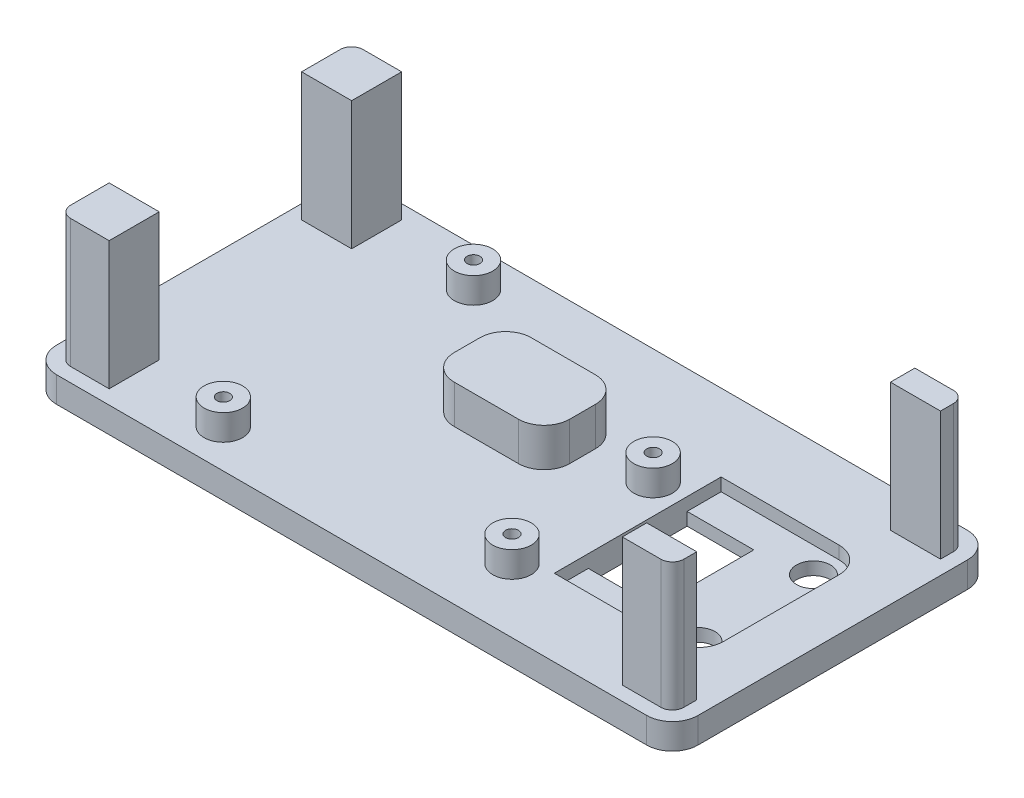
SolidWorks part; units mm, degrees
ref_plane "Front Plane" through (0, 0, 0) normal (0, 0, 1) x (1, 0, 0)
ref_plane "Top Plane" through (0, 0, 0) normal (0, 1, 0) x (1, 0, 0)
ref_plane "Right Plane" through (0, 0, 0) normal (1, 0, 0) x (0, 0, -1)
sketch "Sketch1" plane through (0, 0, 0) normal (0, 1, 0) x (1, 0, 0)
  line L1 (0, 0) -> (127, 0)
  line L2 (0, 0) -> (0, 63.5)
  line L3 (0, 63.5) -> (127, 63.5)
  line L4 (127, 0) -> (127, 63.5)
  dimension "D1" = 127
  dimension "D2" = 63.5
extrude "Boss-Extrude1" add sketch "Sketch1" along normal blind 5.08
sketch "Sketch2" plane through (0, 5.08, 0) normal (0, 1, 0) x (1, 0, 0)
  line L0 (63.5, 63.5) -> (63.5, 0) construction
  line L1 (127, 63.5) -> (0, 63.5) construction
  line L2 (0, 0) -> (127, 0) construction
  line L3 (0, 31.75) -> (127, 31.75) construction
  line L4 (0, 63.5) -> (0, 0) construction
  line L5 (127, 0) -> (127, 63.5) construction
  line L6 (12.7, 2.794) -> (12.7, 12.7)
  line L7 (2.794, 60.706) -> (12.7, 60.706)
  line L8 (2.794, 60.706) -> (2.794, 50.8)
  line L9 (2.794, 50.8) -> (12.7, 50.8)
  line L10 (12.7, 60.706) -> (12.7, 50.8)
  line L11 (2.794, 12.7) -> (12.7, 12.7)
  line L12 (2.794, 2.794) -> (2.794, 12.7)
  line L13 (2.794, 2.794) -> (12.7, 2.794)
  line L14 (124.206, 2.794) -> (124.206, 7.62)
  line L15 (114.3, 60.706) -> (124.206, 60.706)
  line L16 (114.3, 60.706) -> (114.3, 55.88)
  line L17 (114.3, 55.88) -> (124.206, 55.88)
  line L18 (124.206, 60.706) -> (124.206, 55.88)
  line L19 (114.3, 7.62) -> (124.206, 7.62)
  line L20 (114.3, 2.794) -> (114.3, 7.62)
  line L21 (114.3, 2.794) -> (124.206, 2.794)
  dimension "D1" = 9.906
  dimension "D2" = 9.906
  dimension "D3" = 2.794
  dimension "D4" = 2.794
  dimension "D5" = 2.794
  dimension "D6" = 2.794
  dimension "D7" = 4.826
  dimension "D8" = 9.906
extrude "Boss-Extrude3" add sketch "Sketch2" along normal blind 25.4
fillet "Fillet3" radius 2.286 4 edges at (124.206, 17.78, -60.706) (124.206, 17.78, -2.794) (2.794, 17.78, -2.794) (2.794, 17.78, -60.706)
fillet "Fillet4" radius 5.08 4 edges at (0, 2.54, -63.5) (127, 2.54, -63.5) (127, 2.54, 0) (0, 2.54, 0)
sketch "Sketch4" plane through (0, 5.08, 0) normal (0, 1, 0) x (1, 0, 0)
  circle A0 centre (31.75, 55.88) radius 3.81
  circle A1 centre (30.48, 7.62) radius 3.81
  circle A2 centre (82.55, 40.64) radius 3.81
  circle A3 centre (82.55, 12.7) radius 3.81
  circle A4 centre (31.75, 55.88) radius 1.27
  circle A5 centre (82.55, 40.64) radius 1.27
  circle A6 centre (30.48, 7.62) radius 1.27
  circle A7 centre (82.55, 12.7) radius 1.27
  dimension "D1" = 7.62
  dimension "D2" = 7.62
  dimension "D7" = 50.8
  dimension "D11" = 7.62
  dimension "D12" = 7.62
  dimension "D13" = 2.54
  dimension "D8" = 2.54
  dimension "D14" = 2.54
  dimension "D15" = 2.54
  dimension "D3" = 15.24
  dimension "D4" = 19.05
  dimension "D5" = 48.26
  dimension "D6" = 7.62
  dimension "D9" = 27.94
  dimension "D10" = 52.07
sketch "Sketch7" plane through (0, 5.08, 0) normal (0, 1, 0) x (1, 0, 0)
  line L0 (121.92, 63.5) -> (5.08, 63.5) construction
  line L1 (48.26, 45.72) -> (71.12, 45.72)
  line L2 (48.26, 45.72) -> (48.26, 30.48)
  line L3 (48.26, 30.48) -> (71.12, 30.48)
  line L4 (71.12, 45.72) -> (71.12, 30.48)
  dimension "D1" = 22.86
  dimension "D2" = 17.78
  dimension "D3" = 30.48
  dimension "D4" = 43.18
sketch "Sketch13" plane through (0, 5.08, 0) normal (0, 1, 0) x (1, 0, 0)
  line L0 (121.92, 63.5) -> (5.08, 63.5) construction
  line L1 (5.08, 0) -> (121.92, 0) construction
  line L2 (127, 5.08) -> (127, 58.42) construction
  line L4 (88.392, 41.529) -> (101.6, 41.529)
  line L5 (88.392, 41.529) -> (88.392, 21.971)
  line L6 (88.392, 21.971) -> (101.6, 21.971)
  line L7 (101.6, 41.529) -> (101.6, 21.971)
  circle A0 centre (111.76, 43.18) radius 3.556
  circle A1 centre (111.76, 20.32) radius 3.556
  dimension "D1" = 7.112
  dimension "D2" = 7.112
  dimension "D3" = 20.32
  dimension "D4" = 20.32
  dimension "D5" = 15.24
  dimension "D6" = 19.558
  dimension "D7" = 13.208
  dimension "D8" = 25.4
  dimension "D9" = 16.891
extrude "Cut-Extrude8" cut sketch "Sketch13" against normal up to next
sketch "Sketch14" plane through (0, 5.08, 0) normal (0, 1, 0) x (1, 0, 0)
  line L0 (88.392, 41.529) -> (88.392, 21.971) construction
  line L1 (88.392, 46.609) -> (101.6, 46.609)
  line L2 (88.392, 46.609) -> (88.392, 16.891)
  line L3 (88.392, 16.891) -> (101.6, 16.891)
  line L4 (101.6, 46.609) -> (101.6, 16.891)
  line L5 (101.6, 21.971) -> (101.6, 41.529) construction
  dimension "D1" = 5.08
  dimension "D2" = 5.08
extrude "Cut-Extrude9" cut sketch "Sketch14" against normal blind 2.54
sketch "Sketch19" plane through (0, 5.08, 0) normal (0, 1, 0) x (1, 0, 0)
  circle A0 centre (111.76, 43.18) radius 5.08
  circle A1 centre (111.76, 20.32) radius 5.08
  dimension "D1" = 10.16
  dimension "D2" = 10.16
extrude "Cut-Extrude12" cut sketch "Sketch19" against normal blind 2.54
extrude "Boss-Extrude13" add sketch "Sketch4" along normal blind 5.08
extrude "Boss-Extrude14" add sketch "Sketch7" along normal blind 7.62
fillet "Fillet5" radius 5.08 4 edges at (48.26, 8.89, -45.72) (71.12, 8.89, -45.72) (71.12, 8.89, -30.48) (48.26, 8.89, -30.48)
sketch "Sketch21" plane through (0, 5.08, 0) normal (0, 1, 0) x (1, 0, 0)
  line L0 (111.76, 48.26) -> (88.392, 48.26)
  line L1 (88.392, 15.24) -> (88.392, 48.26)
  line L2 (111.76, 15.24) -> (88.392, 15.24)
  line L4 (116.84, 20.32) -> (116.84, 43.18)
  circle A0 centre (111.76, 43.18) radius 5.08 construction
  circle A1 centre (111.76, 43.18) radius 5.08 construction
  circle A2 centre (111.76, 20.32) radius 5.08 construction
  circle A3 centre (111.76, 20.32) radius 5.08 construction
  arc A4 (111.76, 48.26) -> (116.84, 43.18) centre (111.76, 43.18) cw
  arc A5 (111.76, 15.24) -> (116.84, 20.32) centre (111.76, 20.32) ccw
  dimension "D1" = 33.02
  dimension "D2" = 23.368
extrude "Cut-Extrude13" cut sketch "Sketch21" against normal blind 2.54
sketch "Sketch22" plane through (0, 2.54, 0) normal (0, 1, 0) x (1, 0, 0)
  circle A1 centre (111.76, 43.18) radius 4.3291
  circle A2 centre (111.76, 43.18) radius 3.3655
  circle A3 centre (111.76, 20.32) radius 4.5363
  circle A4 centre (111.76, 20.32) radius 3.3655
  dimension "D1" = 6.731
  dimension "D2" = 6.731
extrude "Boss-Extrude15" add sketch "Sketch22" against normal blind 2.54
